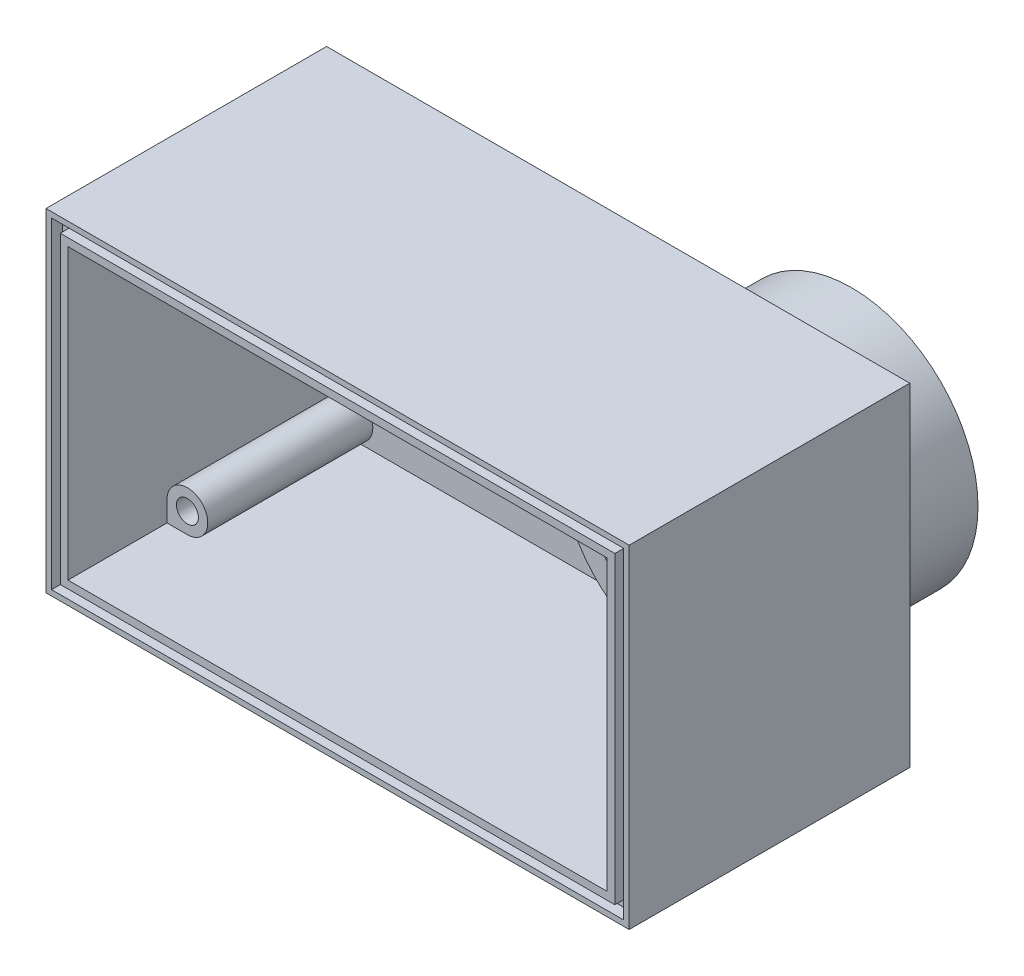
SolidWorks part; units mm, degrees
ref_plane "前视基准面" through (0, 0, 0) normal (0, 0, 1) x (1, 0, 0)
ref_plane "上视基准面" through (0, 0, 0) normal (0, 1, 0) x (1, 0, 0)
ref_plane "右视基准面" through (0, 0, 0) normal (1, 0, 0) x (0, 0, -1)
other "Configuration Table"
sketch "草图1" plane through (0, 0, 0) normal (0, 0, 1) x (1, 0, 0)
  line L1 (-26.5, 15.125) -> (26.5, 15.125)
  line L2 (-26.5, 15.125) -> (-26.5, -15.125)
  line L3 (-26.5, -15.125) -> (26.5, -15.125)
  line L4 (26.5, 15.125) -> (26.5, -15.125)
  line L5 (-26.5, 15.125) -> (26.5, -15.125) construction
  line L6 (-26.5, -15.125) -> (26.5, 15.125) construction
  point P0 (0, 0)
  dimension "D1" = 30.25
  dimension "D2" = 53
extrude "凸台-拉伸1" add sketch "草图1" along normal blind 32
sketch "草图2" plane through (0, 0, 32) normal (0, 0, 1) x (1, 0, 0)
  line L1 (-24.5, 13.125) -> (24.5, 13.125)
  line L2 (-24.5, 13.125) -> (-24.5, -13.125)
  line L3 (-24.5, -13.125) -> (24.5, -13.125)
  line L4 (24.5, 13.125) -> (24.5, -13.125)
  line L5 (-24.5, 13.125) -> (24.5, -13.125) construction
  line L6 (-24.5, -13.125) -> (24.5, 13.125) construction
  point P0 (0, 0)
  dimension "D1" = 26.25
  dimension "D2" = 49
extrude "切除-拉伸1" cut sketch "草图2" against normal blind 24
sketch "草图3" plane through (0, 0, 32) normal (0, 0, 1) x (1, 0, 0)
  line L0 (-25.2, 13.825) -> (25.2, 13.825)
  line L1 (-26, 14.625) -> (26, 14.625)
  line L2 (-26, 14.625) -> (-26, -14.625)
  line L3 (-26, -14.625) -> (26, -14.625)
  line L4 (26, 14.625) -> (26, -14.625)
  line L5 (-26, 14.625) -> (26, -14.625) construction
  line L6 (-26, -14.625) -> (26, 14.625) construction
  line L7 (25.2, 13.825) -> (25.2, -13.825)
  line L8 (-25.2, -13.825) -> (25.2, -13.825)
  line L9 (-25.2, 13.825) -> (-25.2, -13.825)
  point P0 (0, 0)
  dimension "D1" = 29.25
  dimension "D2" = 52
  dimension "D3" = 0.8
extrude "切除-拉伸2" cut sketch "草图3" against normal blind 1
sketch "草图6" plane through (0, 0, 8) normal (0, 0, 1) x (1, 0, 0)
  line L0 (-24.5, 13.125) -> (24.5, 13.125) construction
  line L1 (-24.5, 13.125) -> (-24.5, -13.125) construction
  line L2 (-22.6563, 13.125) -> (-24.5, 13.125)
  line L3 (24.5, 13.125) -> (-24.5, 13.125) construction
  line L4 (-24.5, 13.125) -> (-24.5, 11.2687)
  arc A0 (-22.6563, 13.125) -> (-24.5, 11.2687) centre (-22.65, 11.275) cw
  point P0 (-22.65, 11.275)
  dimension "D1" = 1.85
  dimension "D2" = 1.85
extrude "凸台-拉伸2" add sketch "草图6" along normal blind 15
sketch "草图7" plane through (0, 0, 23) normal (0, 0, 1) x (1, 0, 0)
  circle A0 centre (-22.65, 11.275) radius 1
  dimension "D1" = 2
extrude "切除-拉伸4" cut sketch "草图7" against normal blind 10
mirror "镜向1" about plane through (0, 0, 0) normal (0, 1, 0) of "切除-拉伸4", "凸台-拉伸2"
mirror "镜向2" about plane through (0, 0, 0) normal (1, 0, 0) of "镜向1", "凸台-拉伸2", "切除-拉伸4"
sketch "草图8" plane through (0, 0, 0) normal (0, 0, -1) x (-1, 0, 0)
  line L4 (-26.5, 15.125) -> (-26.5, -15.125)
  line L5 (-26.5, -15.125) -> (26.5, -15.125)
  line L6 (26.5, -15.125) -> (26.5, 15.125)
  line L7 (26.5, 15.125) -> (-26.5, 15.125)
  line L8 (-26.5, 15.125) -> (-26.5, -15.125)
  line L9 (-26.5, -15.125) -> (26.5, -15.125)
  line L10 (26.5, -15.125) -> (26.5, 15.125)
  line L11 (26.5, 15.125) -> (-26.5, 15.125)
  dimension "D1" = 0
extrude "切除-拉伸5" cut sketch "草图8" against normal blind 2
sketch "草图10" plane through (0, 0, 2) normal (0, 0, -1) x (-1, 0, 0)
  line L4 (26.5, 15.125) -> (-26.5, 15.125)
  line L5 (-26.5, 15.125) -> (-26.5, -15.125)
  line L6 (-26.5, -15.125) -> (26.5, -15.125)
  line L7 (26.5, -15.125) -> (26.5, 15.125)
  line L8 (26.5, 15.125) -> (-26.5, 15.125)
  line L9 (-26.5, 15.125) -> (-26.5, -15.125)
  line L10 (-26.5, -15.125) -> (26.5, -15.125)
  line L11 (26.5, -15.125) -> (26.5, 15.125)
  dimension "D1" = 0
sketch "草图11" plane through (0, 0, 2) normal (0, 0, -1) x (-1, 0, 0)
  line L0 (-26.5, 15.125) -> (-26.5, -15.125) construction
  circle A0 centre (-12.7, 0) radius 5
  dimension "D2" = 10
  dimension "D1" = 13.8
extrude "切除-拉伸6" cut sketch "草图11" against normal through all
sketch "草图12" plane through (0, 0, 8) normal (0, 0, 1) x (1, 0, 0)
  circle A0 centre (12.7, 0) radius 9.5
  circle A1 centre (12.7, 0) radius 11.5
  dimension "D1" = 19
  dimension "D2" = 23
extrude "凸台-拉伸4" add sketch "草图12" along normal blind 5
sketch "草图13" plane through (0, 0, 8) normal (0, 0, 1) x (1, 0, 0)
  circle A0 centre (12.7, 0) radius 9.5
extrude "切除-拉伸7" cut sketch "草图13" against normal blind 4.5
sketch "草图14" plane through (0, 0, 2) normal (0, 0, -1) x (-1, 0, 0)
  line L1 (-26.5, 15.125) -> (26.5, 15.125)
  line L2 (-26.5, 15.125) -> (-26.5, -15.125)
  line L3 (-26.5, -15.125) -> (26.5, -15.125)
  line L4 (26.5, 15.125) -> (26.5, -15.125)
  circle A0 centre (-12.7, 0) radius 11.5
  dimension "D1" = 23
extrude "切除-拉伸8" cut sketch "草图14" against normal blind 4.5
sketch "草图15" plane through (0, 0, 8) normal (0, 0, 1) x (1, 0, 0)
  line L1 (-26.5, 15.125) -> (-26.5, -15.125) construction
  line L3 (-26.5, -15.125) -> (26.5, -15.125) construction
  circle A0 centre (-12.5, 0.005) radius 1
  circle A1 centre (-12.5, 0.005) radius 2
  point P0 (-12.5, 0.005)
  dimension "D3" = 2
  dimension "D4" = 4
  dimension "D1" = 14
  dimension "D2" = 15.13
extrude "凸台-拉伸5" add sketch "草图15" along normal blind 3
sketch "草图16" plane through (0, 0, 8) normal (0, 0, 1) x (1, 0, 0)
  line L0 (-26.5, 15.125) -> (-26.5, -15.125) construction
  line L1 (-26.5, -15.125) -> (26.5, -15.125) construction
  circle A0 centre (0, 0) radius 1
  circle A1 centre (0, 0) radius 2
  point P0 (0.1, 0)
  dimension "D3" = 2
  dimension "D4" = 4
  dimension "D1" = 26.6
  dimension "D2" = 15.125
extrude "凸台-拉伸6" add sketch "草图16" along normal blind 3
sketch "草图17" plane through (0, 0, 2) normal (0, 0, -1) x (-1, 0, 0)
  circle A0 centre (-12.7, 0) radius 11.5
  circle A1 centre (-12.7, 0) radius 7
  dimension "D1" = 14
sketch "草图18" plane through (0, 0, 2) normal (0, 0, -1) x (-1, 0, 0)
  circle A0 centre (-12.7, 0) radius 11.5
  circle A1 centre (-12.7, 0) radius 7
  dimension "D1" = 14
extrude "凸台-拉伸8" add sketch "草图18" along normal blind 2
sketch "草图19" plane through (0, 0, 0) normal (0, 0, -1) x (-1, 0, 0)
  circle A0 centre (-12.7, 0) radius 5
  circle A1 centre (-12.7, 0) radius 11.5
extrude "凸台-拉伸9" add sketch "草图19" along normal blind 2
